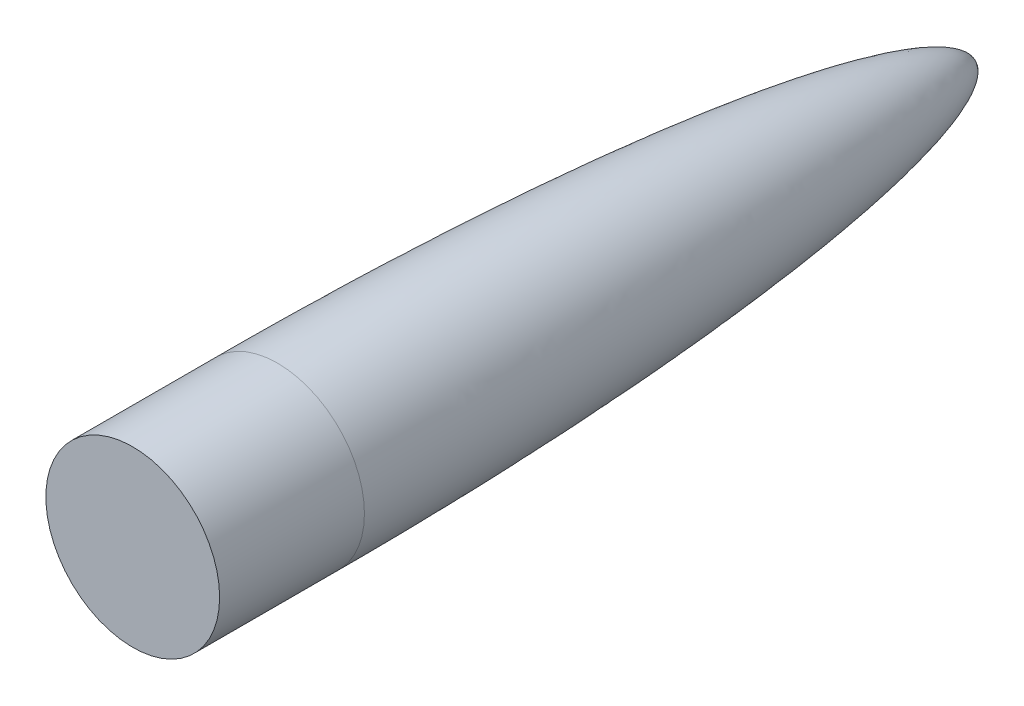
SolidWorks part; units mm, degrees
other "Markup1"
sketch "Sketch3" plane through (-76.2, 76.2, -762) normal (-0.6807, 0.6563, -0.3256) x (-0.115, 0.3432, 0.9322)
ref_plane "Front Plane" through (0, 0, 0) normal (0, 0, 1) x (1, 0, 0)
ref_plane "Top Plane" through (0, 0, 0) normal (0, 1, 0) x (1, 0, 0)
ref_plane "Right Plane"
sketch "Sketch1" plane through (0, 0, 0) normal (1, 0, 0) x (0, 0, -1)
  line L0 (0, 76.2) -> (0, 0)
  line L1 (0, 0) -> (609.6, 0)
  spline S0 degree 4 poles (-60.965, 75.818) (-59.0311, 75.842) (-55.2956, 75.8878) (-49.4551, 75.9506) (-42.0006, 76.0222) (-34.161, 76.0818) (-26.8736, 76.1295) (-18.7209, 76.1653) (-11.9765, 76.1891) (-3.4264, 76.2003) (1.9028, 76.2011) (10.5553, 76.1918) (18.8641, 76.1671) (29.4176, 76.1178) (40.9652, 76.0331) (52.7854, 75.9201) (64.4509, 75.7786) (76.2018, 75.6085) (90.8369, 75.3598) (108.4266, 75.0032) (128.9282, 74.5013) (152.3668, 73.8073) (172.866, 73.0917) (190.4371, 72.3984) (208.0036, 71.6392) (231.4228, 70.5374) (263.6125, 68.7996) (304.5565, 66.1515) (351.3007, 62.4436) (397.9752, 57.9313) (438.723, 53.1101) (473.5427, 48.1519) (501.6857, 43.4017) (523.1995, 39.2415) (544.3495, 34.4893) (562.9602, 29.4819) (578.459, 24.3295) (590.0757, 19.3349) (597.0769, 15.5108) (601.3881, 12.5732) (604.1487, 10.2523) (605.9788, 8.3652) (607.2333, 6.7737) (608.1217, 5.3705) (608.7657, 4.0667) (609.2976, 2.5949) (609.5341, 1.4093) (609.5996, 0.5419) (609.6, 0) knots 0 0 0 0 0 0.011128 0.022257 0.033385 0.044514 0.055642 0.06677 0.077899 0.089027 0.097587 0.106146 0.123265 0.140384 0.157503 0.174622 0.191741 0.20886 0.225979 0.260218 0.294456 0.328694 0.362932 0.380051 0.39717 0.431408 0.499884 0.56836 0.636837 0.705313 0.773789 0.808027 0.842265 0.872021 0.901778 0.934628 0.954807 0.967334 0.975548 0.98116 0.985233 0.988367 0.990878 0.992977 0.994918 0.996846 1 1 1 1 1 construction
  spline S1 degree 4 poles (0, 76.2) (1.3348, 76.2) (4.0253, 76.1988) (10.5553, 76.1918) (18.8641, 76.1671) (29.4176, 76.1178) (40.9652, 76.0331) (52.7854, 75.9201) (64.4509, 75.7786) (76.2018, 75.6085) (90.8369, 75.3598) (108.4266, 75.0032) (128.9282, 74.5013) (152.3668, 73.8073) (172.866, 73.0917) (190.4371, 72.3984) (208.0036, 71.6392) (231.4228, 70.5374) (263.6125, 68.7996) (304.5565, 66.1515) (351.3007, 62.4436) (397.9752, 57.9313) (438.723, 53.1101) (473.5427, 48.1519) (501.6857, 43.4017) (523.1995, 39.2415) (544.3495, 34.4893) (562.9602, 29.4819) (578.459, 24.3295) (590.0757, 19.3349) (597.0769, 15.5108) (601.3881, 12.5732) (604.1487, 10.2523) (605.9788, 8.3652) (607.2333, 6.7737) (608.1217, 5.3705) (608.7657, 4.0667) (609.2976, 2.5949) (609.5341, 1.4093) (609.5996, 0.5419) (609.6, 0) knots 0.089027 0.089027 0.089027 0.089027 0.089027 0.097587 0.106146 0.123265 0.140384 0.157503 0.174622 0.191741 0.20886 0.225979 0.260218 0.294456 0.328694 0.362932 0.380051 0.39717 0.431408 0.499884 0.56836 0.636837 0.705313 0.773789 0.808027 0.842265 0.872021 0.901778 0.934628 0.954807 0.967334 0.975548 0.98116 0.985233 0.988367 0.990878 0.992977 0.994918 0.996846 1 1 1 1 1
ref_axis "Axis1" through (0, 0, -480.06) along (0, 0, 1)
revolve "Revolve1" add sketch "Sketch1" angle 360 about axis through (0, 0, -480.06) along (0, 0, 1)
sketch "Sketch2" plane through (0, 0, 0) normal (0, 0, 1) x (1, 0, 0)
  circle A0 centre (0, 0) radius 76.2
  dimension "D1" = 152.4
extrude "Boss-Extrude1" add sketch "Sketch2" along normal blind 127
equation "\"BodyTubeRadius\"= 3in"
equation "\"ratio\"= 4"
equation "\"NoseConeLength\"= \"ratio\" * 2 * \"BodyTubeRadius\""
equation "\"D1@Sketch2\"=2*\"BodyTubeRadius\""
equation "\"BodyTubeLength\"=5"
